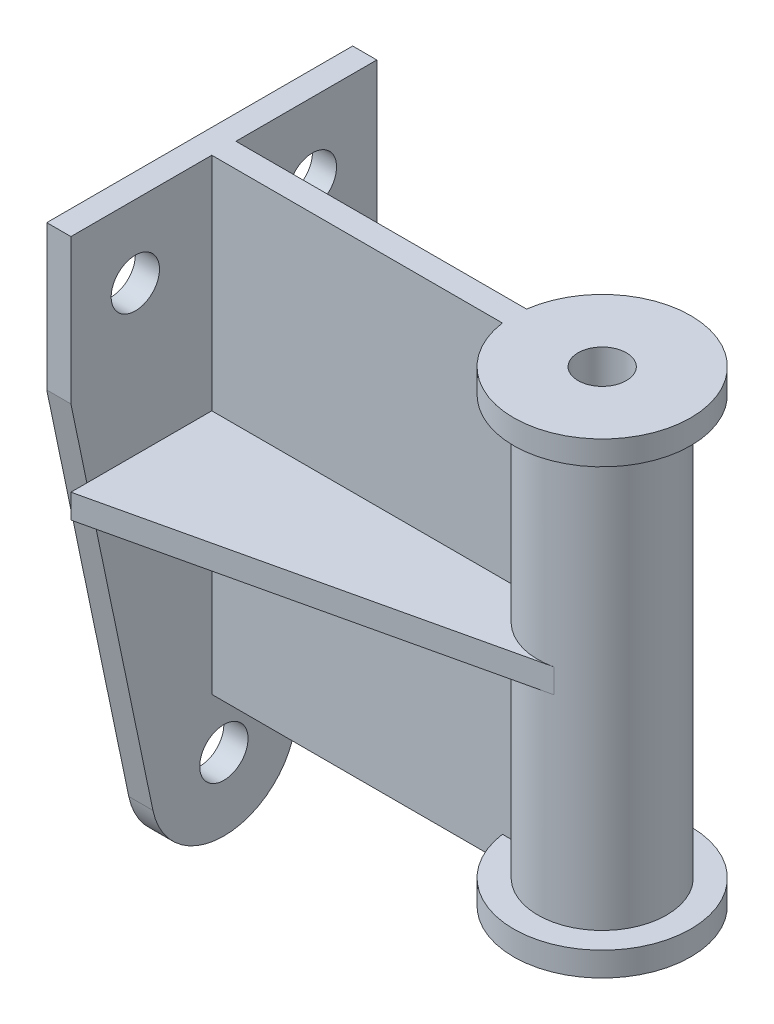
SolidWorks part; units mm, degrees
ref_plane "Front Plane" through (0, 0, 0) normal (0, 0, 1) x (1, 0, 0)
ref_plane "Top Plane" through (0, 0, 0) normal (0, 1, 0) x (1, 0, 0)
ref_plane "Right Plane" through (0, 0, 0) normal (1, 0, 0) x (0, 0, -1)
sketch "Sketch1" plane through (0, 0, 0) normal (0, 1, 0) x (1, 0, 0)
  circle A0 centre (0, 0) radius 16
  circle A1 centre (0, 0) radius 6
  dimension "D1" = 32
  dimension "D2" = 12
extrude "Boss-Extrude1" add sketch "Sketch1" along normal blind 116
sketch "Sketch2" plane through (0, 116, 0) normal (0, 1, 0) x (1, 0, 0)
  circle A0 centre (0, 0) radius 6 construction
  circle A1 centre (0, 0) radius 6
  circle A2 centre (0, 0) radius 22
  dimension "44" = 44
extrude "Boss-Extrude2" add sketch "Sketch2" against normal blind 6
sketch "Sketch3" plane through (0, 0, 0) normal (0, -1, 0) x (1, 0, 0)
  circle A0 centre (0, 0) radius 6 construction
  circle A1 centre (0, 0) radius 22 construction
  circle A2 centre (0, 0) radius 6
  circle A3 centre (0, 0) radius 22
extrude "Boss-Extrude3" add sketch "Sketch3" against normal blind 6
ref_plane "Plane1" through (-100, 0, 0) normal (1, 0, 0) x (0, 0, -1)
sketch "Sketch4" plane through (-100, 0, 0) normal (1, 0, 0) x (0, 0, -1)
  line L0 (-38, 116) -> (38, 116)
  line L1 (-38, 116) -> (-38, 80)
  line L2 (-38, 80) -> (-17.6206, -17.6764)
  line L3 (0, 67.1) -> (0, -67.1) construction
  line L4 (38, 80) -> (17.6206, -17.6764)
  line L5 (38, 116) -> (38, 80)
  line L6 (22, 116) -> (-22, 116) construction
  arc A0 (-17.6206, -17.6764) -> (17.6206, -17.6764) centre (0, -14) ccw
  point P0 (0, 16)
  dimension "D2" = 36
  dimension "D1" = 130
  dimension "D3" = 36
  dimension "D4" = 38
extrude "Boss-Extrude4" add sketch "Sketch4" along normal blind 6 separate body
sketch "Sketch5" plane through (0, 0, 0) normal (0, 0, 1) x (1, 0, 0)
  line L0 (-100, 116) -> (-21, 116)
  line L1 (-100, -41.8) -> (-100, 41.8) construction
  line L2 (-94, 116) -> (-100, 116) construction
  line L3 (-21, 116) -> (-21, 110)
  line L4 (-21, 110) -> (-15, 110)
  line L5 (-15, 110) -> (-15, 6)
  line L6 (-21, 6) -> (-21, 0)
  line L7 (-21, 0) -> (-100, 0)
  line L8 (-100, 0) -> (-100, 116)
  line L9 (-21, 6) -> (-15, 6)
  line L14 (22, 6) -> (-22, 6) construction
  line L15 (-22, 110) -> (22, 110) construction
  point P24 (-16, 5.4962)
  dimension "D1" = 15
  dimension "D2" = 21
extrude "Boss-Extrude7" add sketch "Sketch5" along normal mid plane 6
ref_plane "Plane2" through (0, 58, 0) normal (0, 1, 0) x (1, 0, 0)
sketch "Sketch6" plane through (0, 58, 0) normal (0, 1, 0) x (1, 0, 0)
  line L0 (-94, 38) -> (-94, -38)
  line L1 (-94, -38) -> (3.5806, -15.5942)
  line L2 (-94, 38) -> (3.5806, 15.5942)
  arc A2 (3.5806, 15.5942) -> (3.5806, -15.5942) centre (0, 0) ccw
  point P7 (17.7664, -12.337)
  point P11 (12.7668, 13.4849)
  dimension "D1" = 32
extrude "Boss-Extrude8" add sketch "Sketch6" along normal mid plane 6
hole_wizard "Hole1" positions "Sketch7" profile "Sketch8" legacy end condition through all
sketch "Sketch7" plane through (-94, 0, 0) normal (1, 0, 0) x (0, 0, -1)
  line L0 (-3, 116) -> (-38, 116) construction
  line L1 (-38, 116) -> (-38, 80) construction
  point P0 (0, -14)
  point P5 (-22, 98)
  point P12 (0, 0)
  dimension "D1" = 18
  dimension "D2" = 16
sketch "Sketch8" plane through (-94, -14, 0) normal (0, 1, 0) x (0, 0, -1)
  line L0 (0, 0) -> (0, 6)
  line L1 (0, 6) -> (6, 6)
  line L2 (6, 6) -> (6, 0)
  line L3 (6, 0) -> (0, 0)
  line L4 (0, 110) -> (0, -10) construction
  dimension "Diameter" = 12
  dimension "Depth" = 6
hole_wizard "Hole2" positions "Sketch9" profile "Sketch10" legacy end condition through all
sketch "Sketch9" plane through (-94, 0, 0) normal (1, 0, 0) x (0, 0, -1)
  line L0 (38, 80) -> (38, 116) construction
  line L1 (38, 116) -> (3, 116) construction
  point P0 (22, 98)
  dimension "D1" = 16
  dimension "D2" = 18
sketch "Sketch10" plane through (-94, 98, -22) normal (0, 1, 0) x (0, 0, -1)
  line L0 (0, 0) -> (0, 6)
  line L1 (0, 6) -> (6, 6)
  line L2 (6, 6) -> (6, 0)
  line L3 (6, 0) -> (0, 0)
  line L4 (0, 110) -> (0, -10) construction
  dimension "Diameter" = 12
  dimension "Depth" = 6
